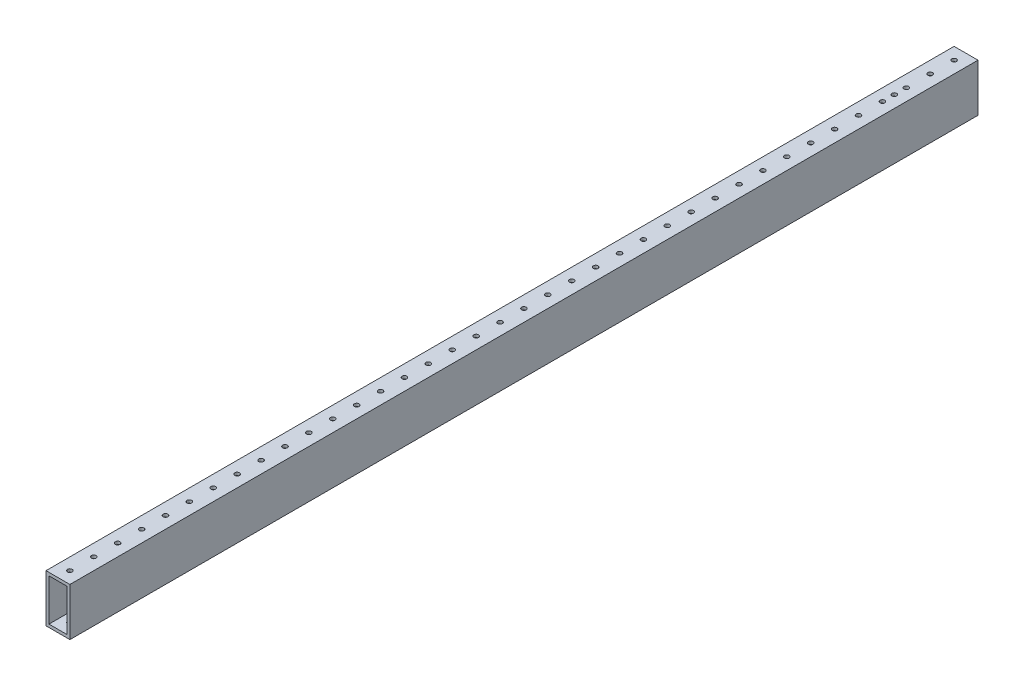
SolidWorks part; units mm, degrees
ref_plane "Front Plane" through (0, 0, 0) normal (0, 0, 1) x (1, 0, 0)
ref_plane "Top Plane" through (0, 0, 0) normal (0, 1, 0) x (1, 0, 0)
ref_plane "Right Plane" through (0, 0, 0) normal (1, 0, 0) x (0, 0, -1)
sketch "Sketch1" plane through (0, 0, 0) normal (0, 0, 1) x (1, 0, 0)
  line L0 (-9.525, -22.225) -> (-9.525, 22.225)
  line L1 (-12.7, -25.4) -> (12.7, -25.4)
  line L2 (-12.7, -25.4) -> (-12.7, 25.4)
  line L3 (-12.7, 25.4) -> (12.7, 25.4)
  line L4 (12.7, -25.4) -> (12.7, 25.4)
  line L5 (-12.7, -25.4) -> (12.7, 25.4) construction
  line L6 (-12.7, 25.4) -> (12.7, -25.4) construction
  line L7 (-9.525, 22.225) -> (9.525, 22.225)
  line L8 (9.525, -22.225) -> (9.525, 22.225)
  line L9 (-9.525, -22.225) -> (9.525, -22.225)
  point P0 (0, 0)
  dimension "D1" = 50.8
  dimension "D2" = 25.4
  dimension "D3" = 3.175
extrude "Boss-Extrude1" add sketch "Sketch1" along normal blind 965.2
sketch "Sketch2" plane through (0, 25.4, 0) normal (0, 1, 0) x (1, 0, 0)
  line L0 (0, 0) -> (0, -965.2) construction
  line L1 (12.7, -965.2) -> (-12.7, -965.2) construction
  line L2 (12.7, 0) -> (-12.7, 0) construction
  circle A0 centre (0, -12.7) radius 2.4892
  circle A1 centre (0, -38.1) radius 2.4892
  circle A2 centre (0, -63.5) radius 2.4892
  circle A3 centre (0, -88.9) radius 2.4892
  circle A4 centre (0, -114.3) radius 2.4892
  circle A5 centre (0, -139.7) radius 2.4892
  circle A6 centre (0, -165.1) radius 2.4892
  circle A7 centre (0, -190.5) radius 2.4892
  circle A8 centre (0, -215.9) radius 2.4892
  circle A9 centre (0, -241.3) radius 2.4892
  circle A10 centre (0, -266.7) radius 2.4892
  circle A11 centre (0, -292.1) radius 2.4892
  circle A12 centre (0, -317.5) radius 2.4892
  circle A13 centre (0, -342.9) radius 2.4892
  circle A14 centre (0, -368.3) radius 2.4892
  circle A15 centre (0, -393.7) radius 2.4892
  circle A16 centre (0, -419.1) radius 2.4892
  circle A17 centre (0, -444.5) radius 2.4892
  circle A18 centre (0, -469.9) radius 2.4892
  circle A19 centre (0, -495.3) radius 2.4892
  circle A20 centre (0, -520.7) radius 2.4892
  circle A21 centre (0, -546.1) radius 2.4892
  circle A22 centre (0, -571.5) radius 2.4892
  circle A23 centre (0, -596.9) radius 2.4892
  circle A24 centre (0, -622.3) radius 2.4892
  circle A25 centre (0, -647.7) radius 2.4892
  circle A26 centre (0, -673.1) radius 2.4892
  circle A27 centre (0, -698.5) radius 2.4892
  circle A28 centre (0, -723.9) radius 2.4892
  circle A29 centre (0, -749.3) radius 2.4892
  circle A30 centre (0, -774.7) radius 2.4892
  circle A31 centre (0, -800.1) radius 2.4892
  circle A32 centre (0, -825.5) radius 2.4892
  circle A33 centre (0, -850.9) radius 2.4892
  circle A34 centre (0, -876.3) radius 2.4892
  circle A35 centre (0, -901.7) radius 2.4892
  circle A36 centre (0, -927.1) radius 2.4892
  circle A37 centre (0, -952.5) radius 2.4892
  circle A38 centre (0, -76.2) radius 2.4892
  dimension "D1" = 4.9784
  dimension "D2" = 12.7
  dimension "D4" = 25.4
  dimension "D5" = 12.7
  dimension "D3" = 38
extrude "Cut-Extrude1" cut sketch "Sketch2" against normal through all
